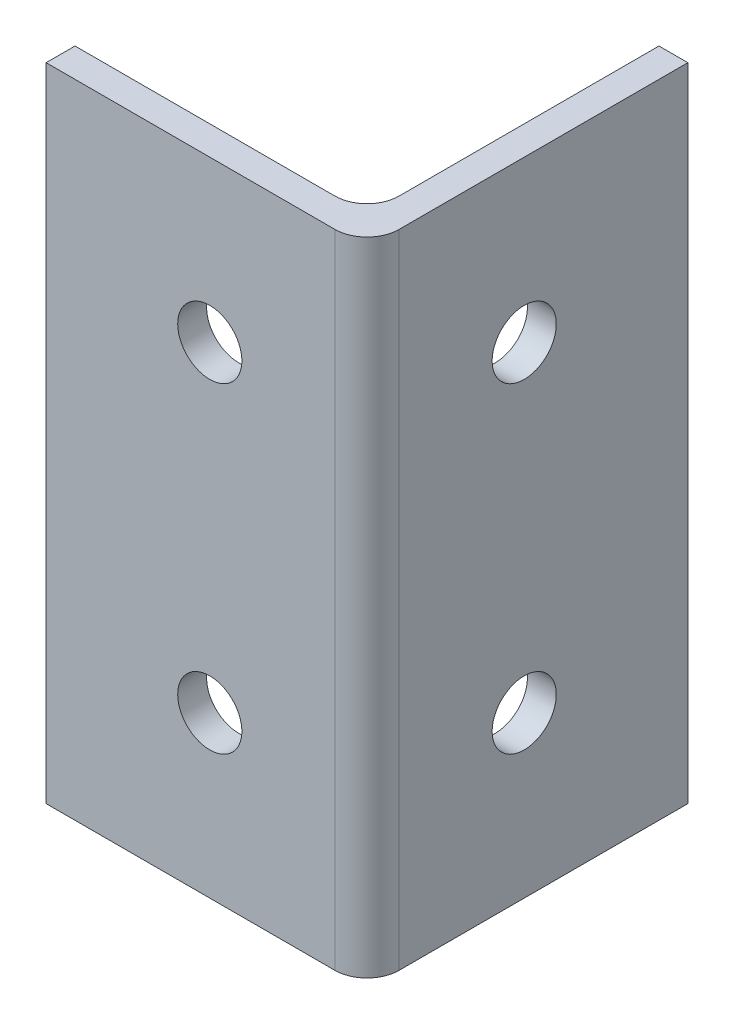
SolidWorks part; units mm, degrees
ref_plane "Front Plane" through (0, 0, 0) normal (0, 0, 1) x (1, 0, 0)
ref_plane "Top Plane" through (0, 0, 0) normal (0, 1, 0) x (1, 0, 0)
ref_plane "Right Plane" through (0, 0, 0) normal (1, 0, 0) x (0, 0, -1)
sketch "Sketch2" plane through (0, 0, 0) normal (0, 1, 0) x (1, 0, 0)
  line L0 (-22.7092, 14.295) -> (-22.7092, -8.819)
  line L1 (-22.7092, 14.295) -> (-20.4232, 14.295)
  line L2 (-20.4232, 14.295) -> (-20.4232, -11.105)
  line L3 (-20.4232, -11.105) -> (-45.8232, -11.105)
  line L4 (-45.8232, -11.105) -> (-45.8232, -8.819)
  line L5 (-45.8232, -8.819) -> (-22.7092, -8.819)
  dimension "D1" = 23.114
  dimension "D2" = 2.286
  dimension "D3" = 25.4
  dimension "D4" = 25.4
  dimension "D5" = 2.286
extrude "Boss-Extrude1" add sketch "Sketch2" along normal blind 50.8
fillet "Fillet1" radius 2.54 1 edges at (-22.7092, 25.4, 8.819)
fillet "Fillet2" radius 2.54 1 edges at (-20.4232, 25.4, 11.105)
sketch "Sketch3" plane through (-22.7092, 0, 0) normal (-1, 0, 0) x (0, 0, 1)
  line L0 (-14.295, 0) -> (6.279, 0) construction
  line L1 (-14.295, 50.8) -> (-14.295, 0) construction
  circle A0 centre (-1.341, 12.7) radius 2.54
  circle A1 centre (-1.341, 38.1) radius 2.54
  dimension "D4" = 5.08
  dimension "D1" = 12.7
  dimension "D2" = 12.954
  dimension "D3" = 2
sketch "Sketch4" plane through (0, 50.8, 0) normal (0, 1, 0) x (1, 0, 0)
  line L0 (-21.1671, -10.3611) -> (-23.4531, -8.0751) construction
  line L1 (-21.1671, -10.3611) -> (-23.4531, -8.0751) construction
  arc A0 (-22.9632, -11.105) -> (-20.4232, -8.565) centre (-22.9632, -8.565) ccw construction
  arc A1 (-25.2492, -8.819) -> (-22.7092, -6.279) centre (-25.2492, -6.279) ccw construction
sketch "Sketch7" plane through (0, 0, 8.819) normal (0, 0, -1) x (-1, 0, 0)
  line L1 (25.2492, 50.8) -> (45.8232, 50.8) construction
  line L2 (45.8232, 50.8) -> (45.8232, 0) construction
  circle A0 centre (32.8692, 38.1) radius 2.54
  circle A1 centre (32.8692, 12.7) radius 2.54
  dimension "D1" = 5.08
  dimension "D2" = 12.7
  dimension "D3" = 12.954
  dimension "D4" = 2
extrude "Cut-Extrude1" cut sketch "Sketch7" against normal blind 50.8
extrude "Cut-Extrude2" cut sketch "Sketch3" against normal blind 50.8
